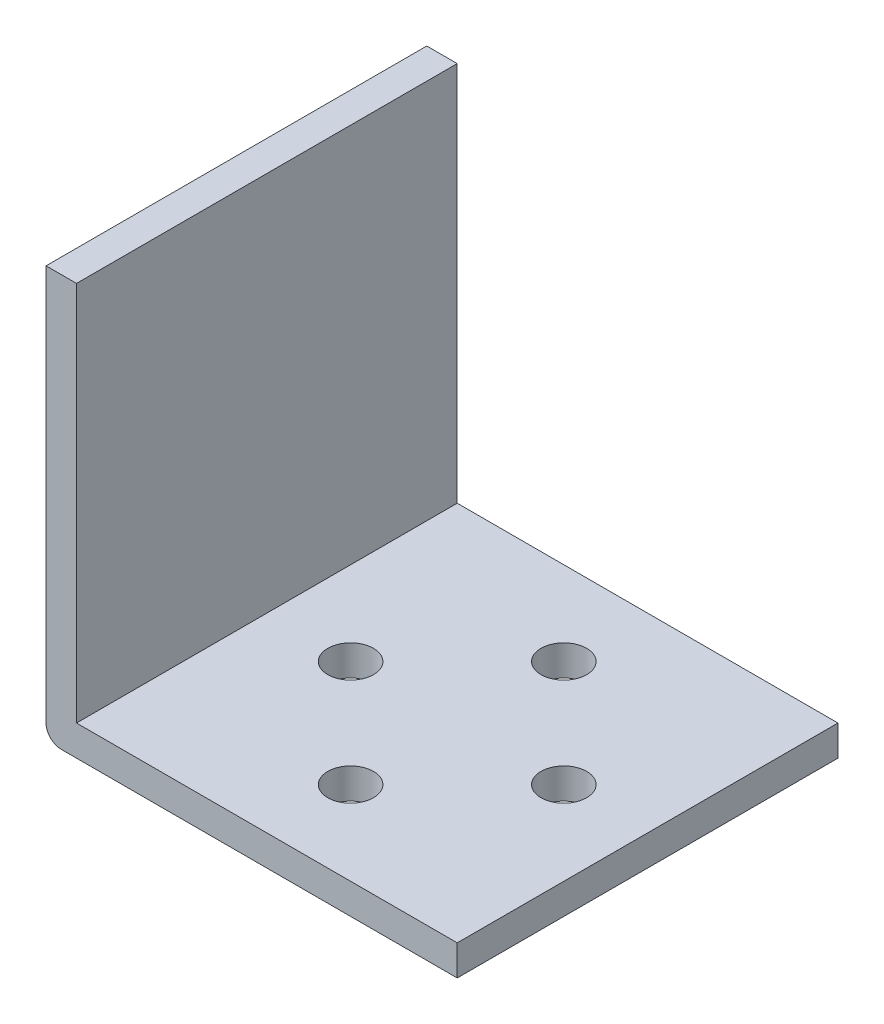
SolidWorks part; units mm, degrees
ref_plane "前视基准面" through (0, 0, 0) normal (0, 0, 1) x (1, 0, 0)
ref_plane "上视基准面" through (0, 0, 0) normal (0, 1, 0) x (1, 0, 0)
ref_plane "右视基准面" through (0, 0, 0) normal (1, 0, 0) x (0, 0, -1)
other "Configuration Table"
sketch "草图1" plane through (0, 0, 0) normal (0, 1, 0) x (1, 0, 0)
  line L1 (-13.5, -12.5) -> (13.5, -12.5)
  line L2 (-13.5, -12.5) -> (-13.5, 12.5)
  line L3 (-13.5, 12.5) -> (13.5, 12.5)
  line L4 (13.5, -12.5) -> (13.5, 12.5)
  line L5 (-13.5, -12.5) -> (13.5, 12.5) construction
  line L6 (-13.5, 12.5) -> (13.5, -12.5) construction
  point P0 (0, 0)
  dimension "D1" = 25
  dimension "D2" = 27
extrude "凸台-拉伸1" add sketch "草图1" along normal blind 2
sketch "草图2" plane through (0, 2, 0) normal (0, 1, 0) x (1, 0, 0)
  line L0 (-13.5, -12.5) -> (13.5, -12.5) construction
  line L1 (-13.5, 12.5) -> (-11.5, 12.5)
  line L2 (-13.5, 12.5) -> (-13.5, -12.5)
  line L3 (-13.5, -12.5) -> (-11.5, -12.5)
  line L4 (-11.5, 12.5) -> (-11.5, -12.5)
  dimension "D1" = 2
extrude "凸台-拉伸2" add sketch "草图2" along normal blind 25
sketch "草图3" plane through (0, 0, 0) normal (0, -1, 0) x (1, 0, 0)
  line L1 (13.5, 12.5) -> (13.5, -12.5) construction
  line L2 (-13.5, 12.5) -> (13.5, 12.5) construction
  circle A0 centre (1, 0) radius 7 construction
  circle A1 centre (1, 7) radius 1.5
  circle A2 centre (8, 0) radius 1.5
  circle A3 centre (1, -7) radius 1.5
  circle A4 centre (-6, 0) radius 1.5
  point P5 (7, -2.905)
  point P6 (0, 0)
  point P7 (0, 0)
  point P14 (1, 0)
  point P15 (0, 0)
  point P16 (2.1584, 0.9636)
  point P17 (0, 0)
  point P20 (0, 0)
  point P21 (0, 0)
  point P22 (1, 4.4636)
  point P23 (0.8047, 0.7964)
  point P24 (0, 0)
  point P25 (3.0805, 2.0496)
  point P26 (1, 0)
  point P27 (1, -0.3373)
  dimension "D1" = 14
  dimension "D2" = 3
  dimension "D4" = 12.5
  dimension "D5" = 12.5
  dimension "D3" = 4
extrude "切除-拉伸1" cut sketch "草图3" against normal through all
fillet "圆角1" radius 1 1 edges at (-13.5, 0, 0)
